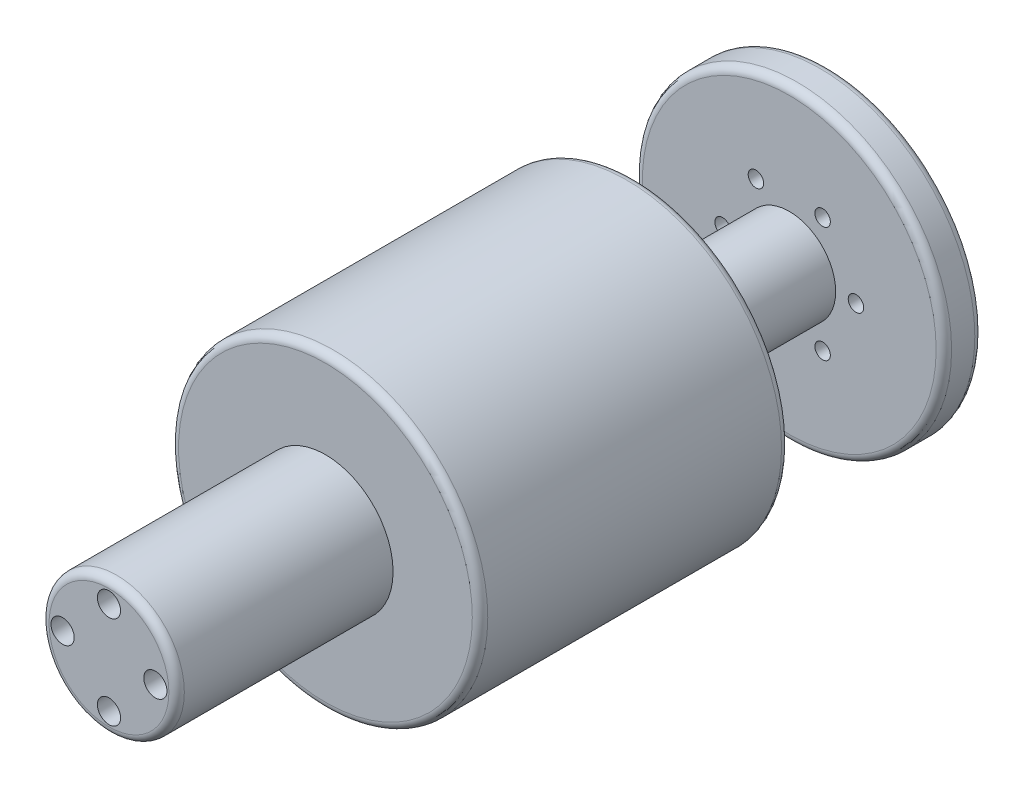
SolidWorks part; units mm, degrees
ref_plane "前视基准面" through (0, 0, 0) normal (0, 0, 1) x (1, 0, 0)
ref_plane "上视基准面" through (0, 0, 0) normal (0, 1, 0) x (1, 0, 0)
ref_plane "右视基准面" through (0, 0, 0) normal (1, 0, 0) x (0, 0, -1)
sketch "草图1" plane through (0, 0, 0) normal (0, 0, 1) x (1, 0, 0)
  circle A0 centre (0, 0) radius 40
  circle A1 centre (0, 0) radius 17.25
  circle A2 centre (-17.25, 0) radius 2
  circle A3 centre (-8.625, 14.9389) radius 2
  circle A4 centre (8.625, 14.9389) radius 2
  circle A5 centre (17.25, 0) radius 2
  circle A6 centre (8.625, -14.9389) radius 2
  circle A7 centre (-8.625, -14.9389) radius 2
  point P18 (0, 0)
  dimension "D1" = 34.5
  dimension "D2" = 6
  dimension "D3" = 80
extrude "凸台-拉伸2" add sketch "草图1" along normal blind 10 contours A0 A7 A1 A2 A3 A4 A5 A6 | A7 A1 A6 A5 A4 A3 A2
sketch "草图3" plane through (0, 0, 10) normal (0, 0, 1) x (1, 0, 0)
  line L0 (0, 35) -> (0, -35)
  circle A0 centre (0, 0) radius 12
  dimension "D1" = 24
  dimension "D2" = 70
  dimension "D3" = 35
extrude "凸台-拉伸4" add sketch "草图3" along normal blind 40 contours A0
sketch "草图4" plane through (0, 0, 50) normal (0, 0, 1) x (1, 0, 0)
  circle A0 centre (0, 0) radius 40
extrude "凸台-拉伸7" add sketch "草图4" along normal blind 80
sketch "草图7" plane through (0, 0, 130) normal (0, 0, 1) x (1, 0, 0)
  circle A0 centre (0, 0) radius 17.5
extrude "凸台-拉伸8" add sketch "草图7" along normal blind 56
sketch "草图9" plane through (0, 0, 0) normal (0, 1, 0) x (1, 0, 0)
  line L0 (40, -50) -> (-40, -50) construction
  circle A0 centre (0, -90) radius 3
  circle A1 centre (0, -70) radius 3
  circle A2 centre (0, -110) radius 3
  dimension "D1" = 6
  dimension "D2" = 40
  dimension "D3" = 2
  dimension "D4" = 2
extrude "切除-拉伸2" cut sketch "草图9" against normal blind 100
sketch "草图11" plane through (0, 0, 186) normal (0, 0, 1) x (1, 0, 0)
  circle A0 centre (0, 0) radius 12
  circle A1 centre (-12, 0) radius 3
extrude "切除-拉伸4" cut sketch "草图11" against normal blind 20 contours A0 A1 | A0 A1
pattern_circular "阵列(圆周)1" count 4 over 360 about axis through (0, 0, 0) along (0, 0, 1) of "切除-拉伸4"
fillet "圆角1" radius 2 5 edges at (17.5, 0, 186) (40, 0, 130) (40, 0, 50) (40, 0, 10) (40, 0, 0)
